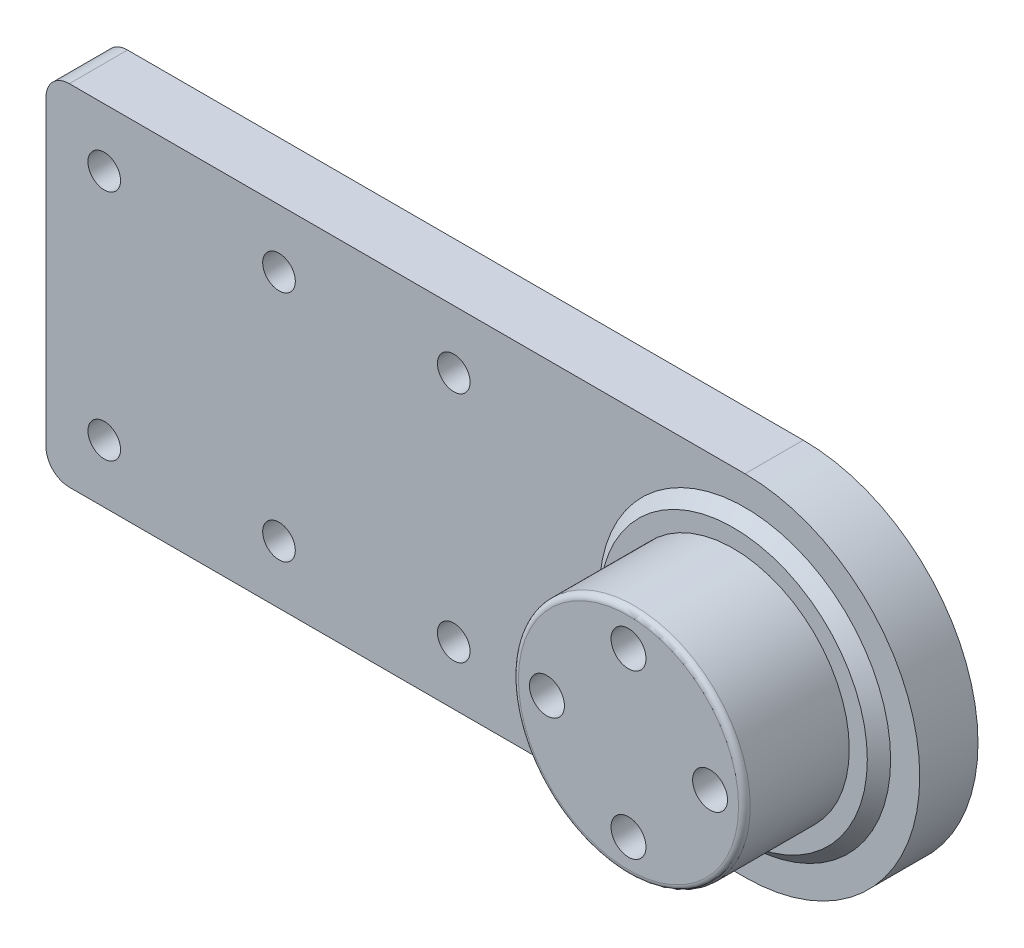
SolidWorks part; units mm, degrees
ref_plane "Front Plane" through (0, 0, 0) normal (0, 0, 1) x (1, 0, 0)
ref_plane "Top Plane" through (0, 0, 0) normal (0, 1, 0) x (1, 0, 0)
ref_plane "Right Plane" through (0, 0, 0) normal (1, 0, 0) x (0, 0, -1)
sketch "Sketch1" plane through (0, 0, 0) normal (0, 1, 0) x (1, 0, 0)
  line L0 (0, 0) -> (9.95, 0)
  line L1 (9.95, 0) -> (9.95, 7)
  line L2 (9.95, 7) -> (11.5, 7)
  line L3 (11.5, 7) -> (12.5, 8)
  line L5 (12.5, 8) -> (0, 8)
  line L6 (0, 0) -> (0, 8) construction
  line L7 (0, 0) -> (0, 8)
  dimension "D1" = 19.9
  dimension "D2" = 7
  dimension "D3" = 23
  dimension "D4" = 1
  dimension "D5" = 1
revolve "Revolve1" add sketch "Sketch1" angle 360 about L6
sketch "Sketch2" plane through (0, 0, -8) normal (0, 0, -1) x (-1, 0, 0)
  line L0 (0, 15) -> (60, 15)
  line L1 (60, 15) -> (60, -15)
  line L2 (60, -15) -> (0, -15)
  arc A0 (0, 15) -> (0, -15) centre (0, 0) ccw
  dimension "D1" = 60
  dimension "D2" = 15
extrude "Boss-Extrude1" add sketch "Sketch2" along normal blind 5 contours L0 L1 L2 A0
sketch "Sketch3" plane through (0, 0, 0) normal (0, 0, 1) x (1, 0, 0)
  circle A0 centre (0, 0) radius 9.95 construction
  circle A1 centre (0, 0) radius 9.95
extrude "Boss-Extrude2" add sketch "Sketch3" along normal blind 2
sketch "Sketch4" plane through (0, 0, 2) normal (0, 0, 1) x (1, 0, 0)
  line L0 (0, 7) -> (0, 0) construction
  circle A0 centre (0, 7) radius 1.5
  circle A1 centre (0, 7) radius 3 construction
  circle A2 centre (7, 0) radius 1.5
  circle A3 centre (0, -7) radius 1.5
  circle A4 centre (-7, 0) radius 1.5
  point P14 (0, 0)
  dimension "D1" = 6
  dimension "D2" = 3
  dimension "D3" = 7
  dimension "D4" = 4
extrude "Cut-Extrude1" cut sketch "Sketch4" against normal through all
sketch "Sketch5" plane through (0, 0, -8) normal (0, 0, 1) x (1, 0, 0)
  line L0 (-55, 10) -> (-55, -10) construction
  line L1 (0, 15) -> (-60, 15) construction
  line L2 (-60, -15) -> (0, -15) construction
  line L3 (-60, 15) -> (-60, -15) construction
  circle A0 centre (-55, 10) radius 1.4
  circle A1 centre (-55, -10) radius 1.4
  circle A2 centre (-40, 10) radius 1.4
  circle A3 centre (-40, -10) radius 1.4
  circle A4 centre (-25, 10) radius 1.4
  circle A5 centre (-25, -10) radius 1.4
  dimension "D4" = 2.8
  dimension "D1" = 5
  dimension "D2" = 5
  dimension "D3" = 5
  dimension "D6" = 15
  dimension "D5" = 3
extrude "Cut-Extrude2" cut sketch "Sketch5" against normal through all
fillet "Fillet1" radius 2 2 edges at (-60, -15, -10.5) (-60, 15, -10.5)
fillet "Fillet2" radius 0.5 1 edges at (9.95, 0, 2)
